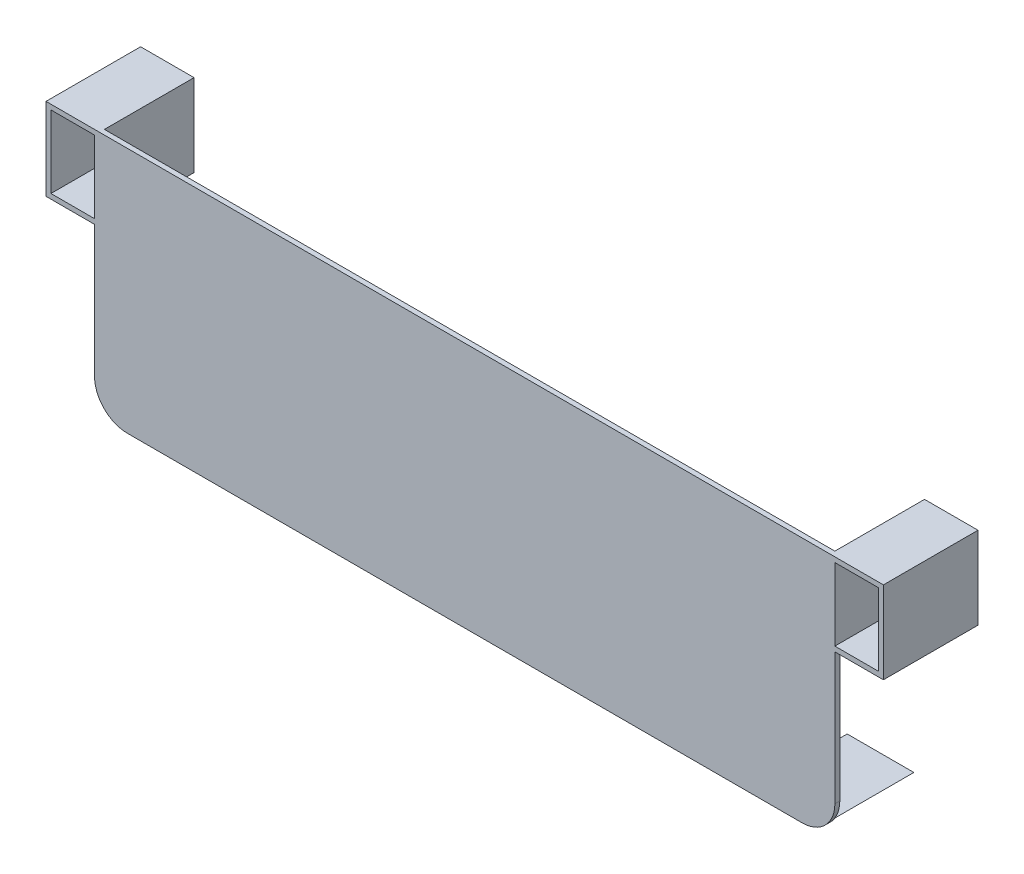
SolidWorks part; units mm, degrees
ref_plane "Alzado" through (0, 0, 0) normal (0, 0, 1) x (1, 0, 0)
ref_plane "Planta" through (0, 0, 0) normal (0, 1, 0) x (1, 0, 0)
ref_plane "Vista lateral" through (0, 0, 0) normal (1, 0, 0) x (0, 0, -1)
sketch "Croquis1" plane through (0, 0, 0) normal (0, 0, 1) x (1, 0, 0)
  line L1 (-214.8473, 47.9032) -> (-34.8473, 47.9032)
  line L2 (-214.8473, 47.9032) -> (-214.8473, -12.0968)
  line L3 (-214.8473, -12.0968) -> (-34.8473, -12.0968)
  line L4 (-34.8473, 47.9032) -> (-34.8473, -12.0968)
  line L5 (-211.8473, -9.0968) -> (-206.2357, -9.0968) construction
  line L8 (-211.8473, 44.9032) -> (-126.4857, -9.0968) construction
  line L9 (-211.8473, -9.0968) -> (-126.4857, 44.9032) construction
  line L19 (-166.3607, 19.6782) -> (-125.3878, -6.2414) construction
  line L20 (-166.3607, 16.1283) -> (-125.3878, 42.0479) construction
  line L21 (-126.4857, -9.0968) -> (-126.4857, 44.9032) construction
  line L25 (-124.8473, -12.0968) -> (-124.8473, 47.9032) construction
  line L26 (-123.2088, -9.0968) -> (-123.2088, 44.9032) construction
  line L27 (-83.3338, 16.1283) -> (-124.3067, 42.0479) construction
  line L28 (-83.3338, 19.6782) -> (-124.3067, -6.2414) construction
  line L29 (-37.8473, -9.0968) -> (-123.2088, 44.9032) construction
  line L30 (-37.8473, 44.9032) -> (-123.2088, -9.0968) construction
  line L31 (-37.8473, -9.0968) -> (-43.4588, -9.0968) construction
  line L43 (-34.8473, 47.9032) -> (-34.8473, -12.0968)
  dimension "D1" = 180
  dimension "D2" = 60
  dimension "D4" = 3
  dimension "D5" = 3
  dimension "D7" = 79.75
extrude "Saliente-Extruir1" add sketch "Croquis1" along normal blind 1.2
sketch "Croquis2" plane through (0, 0, 1.2) normal (0, 0, 1) x (1, 0, 0)
  line L1 (-214.8473, -12.0968) -> (-194.8473, -12.0968)
  line L2 (-214.8473, -12.0968) -> (-214.8473, -10.8968)
  line L3 (-214.8473, -10.8968) -> (-194.8473, -10.8968)
  line L4 (-194.8473, -12.0968) -> (-194.8473, -10.8968)
  line L10 (-124.8473, -12.0968) -> (-124.8473, 47.9032) construction
  line L11 (-214.8473, -12.0968) -> (-34.8473, -12.0968) construction
  line L12 (-214.8473, 47.9032) -> (-34.8473, 47.9032) construction
  line L22 (-213.6473, 47.9032) -> (-226.6473, 47.9032)
  line L23 (-213.6473, 47.9032) -> (-213.6473, 27.9032)
  line L24 (-213.6473, 27.9032) -> (-226.6473, 27.9032)
  line L25 (-226.6473, 47.9032) -> (-226.6473, 27.9032)
  line L26 (-214.8473, 47.9032) -> (-214.8473, -12.0968) construction
  line L27 (-225.4473, 46.7032) -> (-214.8473, 46.7032)
  line L28 (-225.4473, 46.7032) -> (-225.4473, 29.1032)
  line L29 (-225.4473, 29.1032) -> (-214.8473, 29.1032)
  line L31 (-34.8473, 46.7032) -> (-34.8473, 29.1032)
  line L32 (-24.2473, 29.1032) -> (-34.8473, 29.1032)
  line L33 (-24.2473, 46.7032) -> (-24.2473, 29.1032)
  line L34 (-24.2473, 46.7032) -> (-34.8473, 46.7032)
  line L35 (-23.0473, 47.9032) -> (-23.0473, 27.9032)
  line L36 (-36.0473, 27.9032) -> (-23.0473, 27.9032)
  line L37 (-36.0473, 47.9032) -> (-36.0473, 27.9032)
  line L38 (-36.0473, 47.9032) -> (-23.0473, 47.9032)
  line L39 (-54.8473, -12.0968) -> (-54.8473, -10.8968)
  line L40 (-34.8473, -10.8968) -> (-54.8473, -10.8968)
  line L41 (-34.8473, -12.0968) -> (-34.8473, -10.8968)
  line L42 (-34.8473, -12.0968) -> (-54.8473, -12.0968)
  line L43 (-214.8473, 47.9032) -> (-214.8473, -12.0968) construction
  line L44 (-214.8473, 46.7032) -> (-214.8473, 29.1032)
  dimension "D1" = 20
  dimension "D2" = 20
  dimension "D3" = 13
  dimension "D4" = 1.2
  dimension "D5" = 1.2
  dimension "D6" = 1.2
  dimension "D7" = 1.2
  dimension "D8" = 1.2
extrude "Saliente-Extruir2" add sketch "Croquis2" against normal blind 23
fillet "Redondeo1" radius 8 2 edges at (-34.8473, -12.0968, -10.3) (-214.8473, -12.0968, -10.3)
